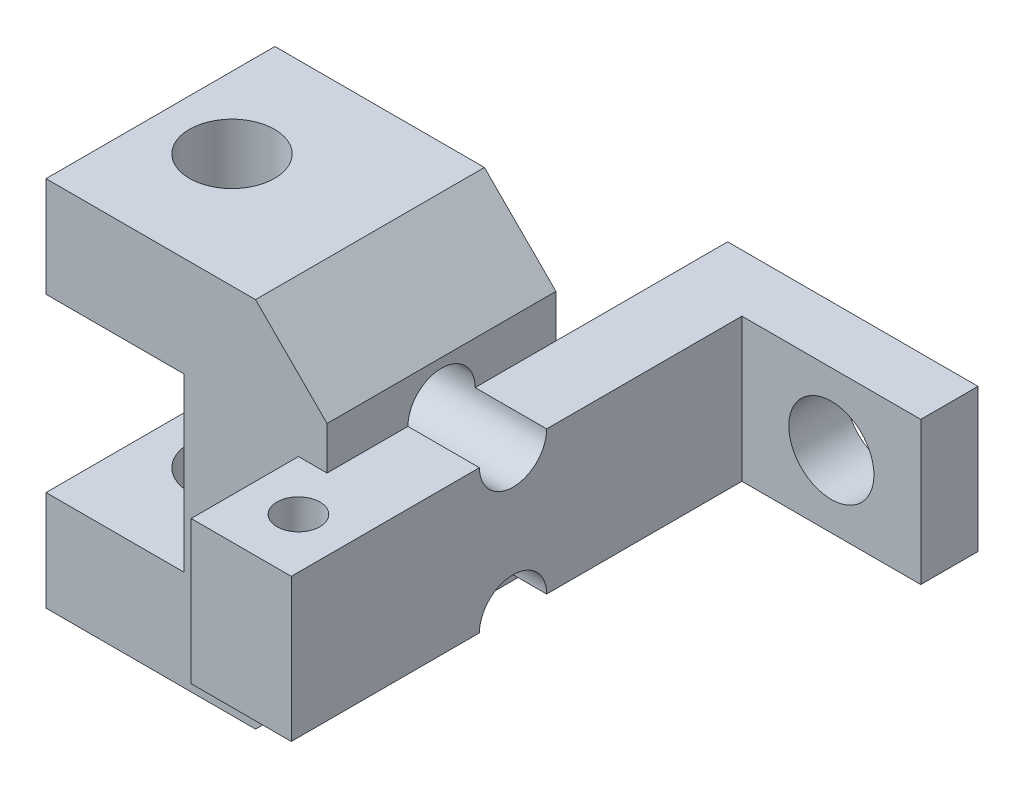
SolidWorks part; units mm, degrees
material "Delrin 2700 NC010, Low Viscosity Acetal Copolymer (SS)"
ref_plane "Front Plane" through (0, 0, 0) normal (0, 0, 1) x (1, 0, 0)
ref_plane "Top Plane" through (0, 0, 0) normal (0, 1, 0) x (1, 0, 0)
ref_plane "Right Plane" through (0, 0, 0) normal (1, 0, 0) x (0, 0, -1)
sketch "Sketch1" plane through (0, 0, 0) normal (0, 0, 1) x (1, 0, 0)
  line L0 (0, 0) -> (-2.45, 0)
  line L1 (-2.45, 0) -> (-2.45, 1.778)
  line L2 (-2.45, 1.778) -> (0, 1.778)
  line L3 (0, 1.778) -> (0, 4.826)
  line L4 (0, 4.826) -> (-2.45, 4.826)
  line L5 (-2.45, 4.826) -> (-2.45, 6.604)
  line L6 (-2.45, 6.604) -> (0, 6.604)
  line L7 (0, 0) -> (1.27, 0)
  line L8 (2.54, 5.334) -> (2.54, 1.27)
  line L9 (1.27, 6.604) -> (0, 6.604) construction
  line L10 (0, 6.604) -> (1.27, 6.604)
  line L11 (1.27, 0) -> (2.54, 1.27)
  line L12 (1.27, 6.604) -> (2.54, 5.334)
  dimension "D1" = 2.45
  dimension "D2" = 1.778
  dimension "D3" = 3.048
  dimension "D4" = 1.778
  dimension "D5" = 1.27
  dimension "D6" = 1.27
extrude "Boss-Extrude1" add sketch "Sketch1" along normal blind 4.064
sketch "Sketch14" plane through (2.54, 0, 0) normal (1, 0, 0) x (0, 0, -1)
  line L0 (-4.064, 2.032) -> (-4.064, 1.27) construction
  line L1 (-5.969, 4.572) -> (3.048, 4.572)
  line L5 (-4.064, 2.032) -> (3.048, 2.032) construction
  line L7 (-4.064, 2.032) -> (-5.969, 2.032) construction
  line L8 (-5.969, 4.572) -> (-5.969, 2.032)
  line L9 (-5.969, 2.032) -> (3.048, 2.032)
  line L10 (3.048, 2.032) -> (3.048, 4.572)
  dimension "D1" = 2.54
extrude "Boss-Extrude5" add sketch "Sketch14" along normal blind 1.27
sketch "Sketch15" plane through (2.54, 0, 0) normal (-1, 0, 0) x (0, 0, 1)
  line L0 (4.064, 2.032) -> (4.064, 4.572)
  line L1 (4.064, 4.572) -> (5.969, 4.572)
  line L2 (5.969, 4.572) -> (5.969, 2.032)
  line L3 (5.969, 2.032) -> (4.064, 2.032)
extrude "Boss-Extrude6" add sketch "Sketch15" along normal blind 0.508
sketch "Sketch16" plane through (3.81, 0, 0) normal (1, 0, 0) x (0, 0, -1)
  line L0 (3.048, 2.032) -> (3.048, 4.572)
  line L1 (3.048, 4.572) -> (2.032, 4.572)
  line L2 (3.048, 4.572) -> (-5.969, 4.572) construction
  line L3 (2.032, 4.572) -> (2.032, 2.032)
  line L4 (-5.969, 2.032) -> (3.048, 2.032) construction
  line L5 (2.032, 2.032) -> (3.048, 2.032)
extrude "Boss-Extrude7" add sketch "Sketch16" along normal blind 3.175
sketch "Sketch17" plane through (0, 0, -3.048) normal (0, 0, -1) x (-1, 0, 0)
  circle A0 centre (-5.3975, 3.302) radius 0.7557
  dimension "D1" = 1.5113
extrude "Cut-Extrude6" cut sketch "Sketch17" against normal blind 3.175
sketch "Sketch18" plane through (0, 2.032, 0) normal (0, -1, 0) x (1, 0, 0)
  circle A0 centre (2.921, 4.953) radius 0.381
extrude "Cut-Extrude7" cut sketch "Sketch18" against normal blind 3.175
sketch "Sketch19" plane through (2.54, 0, 0) normal (1, 0, 0) x (0, 0, -1)
  circle A0 centre (-2.032, 4.572) radius 0.5969
  circle A1 centre (-2.032, 2.032) radius 0.5969
extrude "Cut-Extrude9" cut sketch "Sketch19" against normal blind 2.54 and the other way through all
sketch "Sketch20" plane through (0, 6.604, 0) normal (0, 1, 0) x (1, 0, 0)
  line L0 (-2.45, 0) -> (-1.18, 0)
  line L1 (1.27, 0) -> (-2.45, 0) construction
  line L2 (-1.18, 0) -> (-1.18, -2.032)
  circle A0 centre (-1.18, -2.032) radius 0.7556
  dimension "D3" = 1.5113
  dimension "D1" = 1.27
  dimension "D2" = 2.032
extrude "Cut-Extrude10" cut sketch "Sketch20" against normal blind 10
ref_plane "Plane2" through (0, 0, 2.032) normal (0, 0, -1) x (-1, 0, 0)
